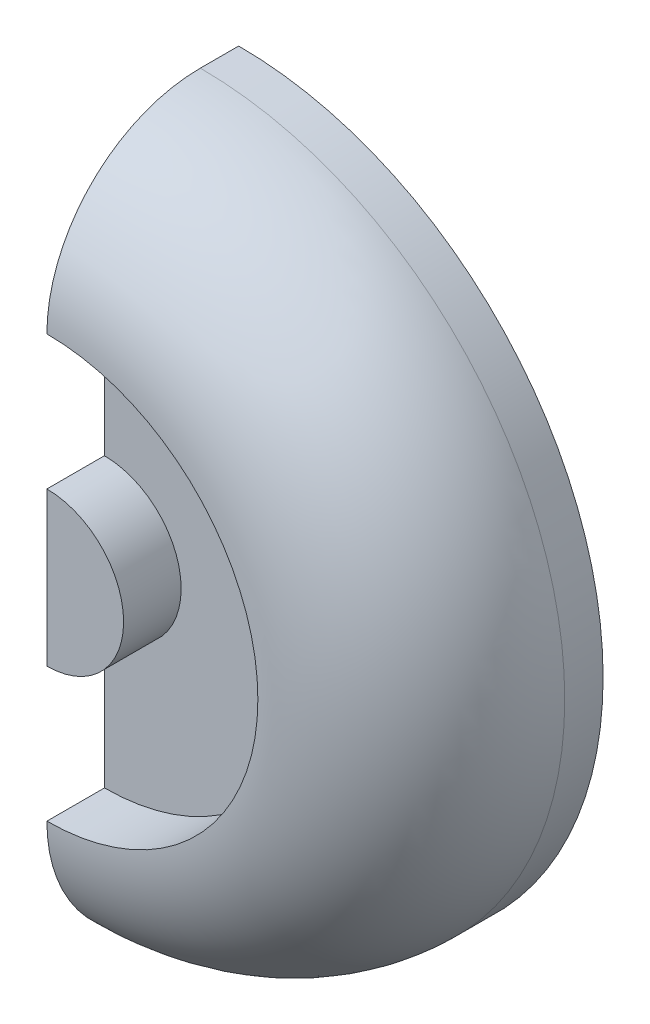
SolidWorks part; units mm, degrees
material "ABS"
ref_plane "Front Plane" through (0, 0, 0) normal (0, 0, 1) x (1, 0, 0)
ref_plane "Top Plane" through (0, 0, 0) normal (0, 1, 0) x (1, 0, 0)
ref_plane "Right Plane" through (0, 0, 0) normal (1, 0, 0) x (0, 0, -1)
sketch "Sketch1" plane through (0, 0, 0) normal (0, 0, 1) x (1, 0, 0)
  circle A0 centre (0, 0) radius 47.5
extrude "Boss-Extrude2" add sketch "Sketch1" along normal blind 25
fillet "Fillet1" radius 20 1 edges at (47.5, 0, 25)
sketch "Sketch3" plane through (0, 0, 25) normal (0, 0, 1) x (1, 0, 0)
  circle A0 centre (0, 0) radius 10
extrude "Boss-Extrude3" add sketch "Sketch3" against normal blind 5
sketch "Sketch4" plane through (0, 0, 25) normal (0, 0, 1) x (1, 0, 0)
  circle A0 centre (0, 0) radius 27.5
extrude "Cut-Extrude1" cut sketch "Sketch4" against normal blind 7.5
sketch "Sketch5" plane through (0, 0, 17.5) normal (0, 0, 1) x (1, 0, 0)
  circle A0 centre (0, 0) radius 10
extrude "Boss-Extrude5" add sketch "Sketch5" along normal blind 7.5
sketch "Sketch6" plane through (0, 0, 25) normal (0, 0, 1) x (1, 0, 0)
  line L1 (-48.6823, 51.0554) -> (0, 51.0554)
  line L2 (-48.6823, 51.0554) -> (-48.6823, -54.7167)
  line L3 (-48.6823, -54.7167) -> (0, -54.7167)
  line L4 (0, 51.0554) -> (0, -54.7167)
extrude "Cut-Extrude2" cut sketch "Sketch6" against normal blind 50
scale "Scale4" scale about centroid uniform scaling yes scale factor 1.15
